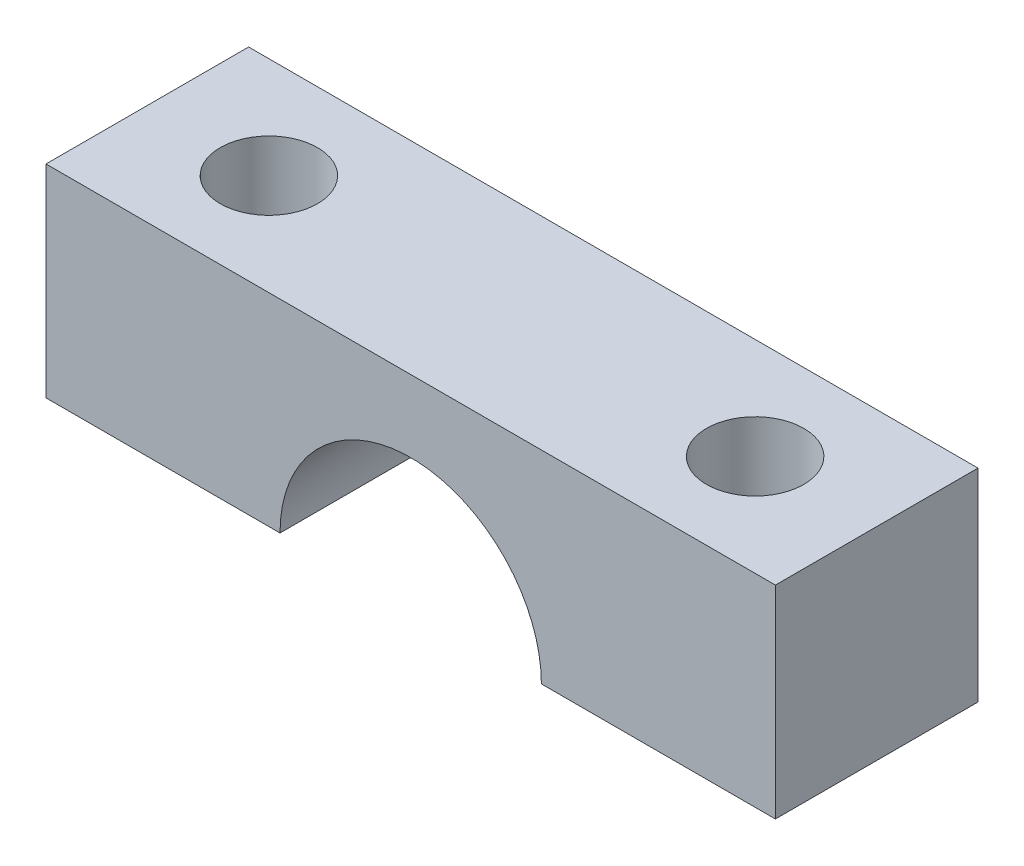
SolidWorks part; units mm, degrees
ref_plane "Front Plane" through (0, 0, 0) normal (0, 0, 1) x (1, 0, 0)
ref_plane "Top Plane" through (0, 0, 0) normal (0, 1, 0) x (1, 0, 0)
ref_plane "Right Plane" through (0, 0, 0) normal (1, 0, 0) x (0, 0, -1)
sketch "Sketch1" plane through (0, 0, 0) normal (0, 0, 1) x (1, 0, 0)
  line L0 (0, 0) -> (0, 5) construction
  line L1 (3.225, 0) -> (9, 0)
  line L2 (9, 0) -> (9, 5)
  line L3 (9, 5) -> (-9, 5)
  line L4 (-9, 0) -> (-9, 5)
  line L5 (-3.225, 0) -> (-9, 0)
  arc A0 (3.225, 0) -> (-3.225, 0) centre (0, 0) ccw
  dimension "D3" = 3.225
  dimension "D1" = 18
  dimension "D2" = 5
extrude "Boss-Extrude1" add sketch "Sketch1" along normal blind 5
sketch "Sketch2" plane through (0, 0, 0) normal (0, 1, 0) x (1, 0, 0)
  line L0 (0, 0) -> (0, -5) construction
  line L1 (9, 0) -> (-9, 0) construction
  line L2 (9, -5) -> (-9, -5) construction
  circle A0 centre (-6, -2.5) radius 1.2
  circle A1 centre (6, -2.5) radius 1.2
  dimension "D1" = 12
  dimension "D2" = 2.5
  dimension "D3" = 2.4
extrude "Cut-Extrude1" cut sketch "Sketch2" along normal through all
